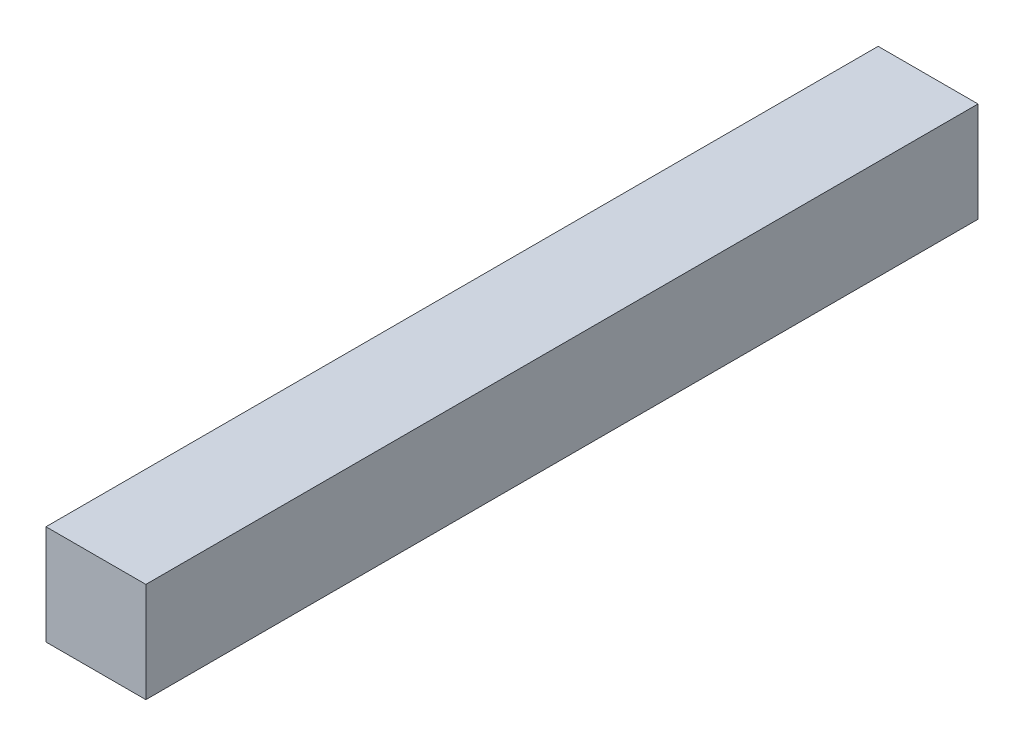
SolidWorks part; units mm, degrees
ref_plane "Front Plane" through (0, 0, 0) normal (0, 0, 1) x (1, 0, 0)
ref_plane "Top Plane" through (0, 0, 0) normal (0, 1, 0) x (1, 0, 0)
ref_plane "Right Plane" through (0, 0, 0) normal (1, 0, 0) x (0, 0, -1)
sketch "Sketch1" plane through (0, 0, 0) normal (0, 0, 1) x (1, 0, 0)
  line L1 (3, -3) -> (-3, -3)
  line L2 (3, -3) -> (3, 3)
  line L3 (3, 3) -> (-3, 3)
  line L4 (-3, -3) -> (-3, 3)
  line L5 (3, -3) -> (-3, 3) construction
  line L6 (3, 3) -> (-3, -3) construction
  point P0 (0, 0)
  dimension "D1" = 6
  dimension "D2" = 6
extrude "Boss-Extrude1" add sketch "Sketch1" along normal blind 50
